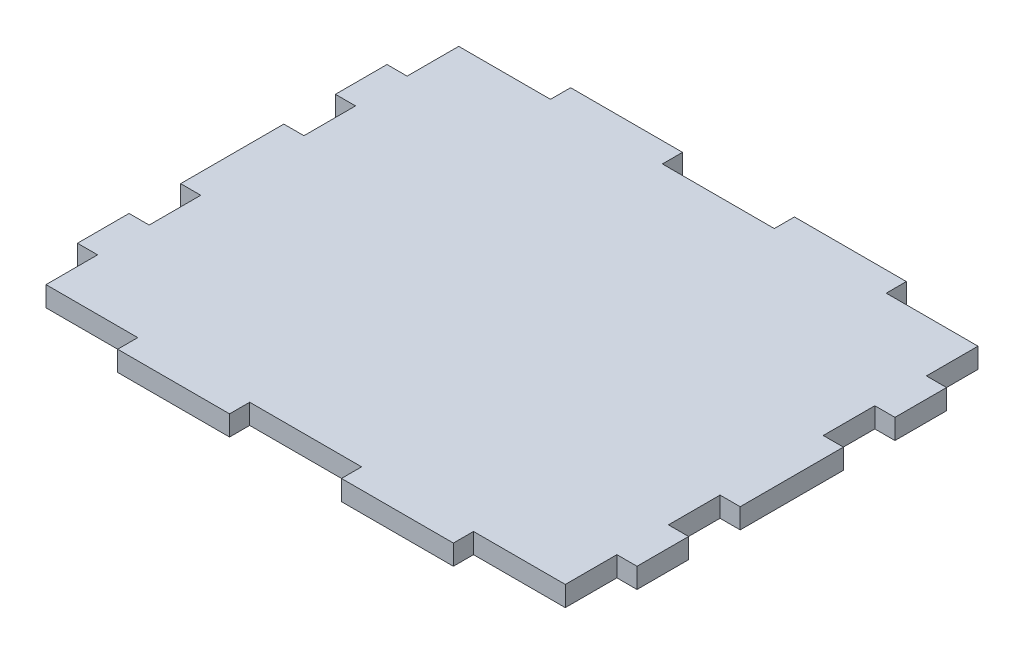
SolidWorks part; units mm, degrees
ref_plane "Front Plane" through (0, 0, 0) normal (0, 0, 1) x (1, 0, 0)
ref_plane "Top Plane" through (0, 0, 0) normal (0, 1, 0) x (1, 0, 0)
ref_plane "Right Plane" through (0, 0, 0) normal (1, 0, 0) x (0, 0, -1)
sketch "Sketch1" plane through (0, 0, 0) normal (0, 1, 0) x (1, 0, 0)
  line L1 (-45.7927, 36.9171) -> (154.7657, 36.9171)
  line L2 (-45.7927, 36.9171) -> (-45.7927, -125.4397)
  line L3 (-45.7927, -125.4397) -> (154.7657, -125.4397)
  line L4 (154.7657, 36.9171) -> (154.7657, -125.4397)
  dimension "D1" = 200.5584
  dimension "D2" = 162.3568
extrude "Boss-Extrude1" add sketch "Sketch1" along normal blind 7.2136
sketch "Sketch2" plane through (0, 7.2136, 0) normal (0, 1, 0) x (1, 0, 0)
  line L0 (54.4865, 36.9171) -> (54.4865, -125.4397) construction
  line L1 (154.7657, 36.9171) -> (-45.7927, 36.9171) construction
  line L2 (-45.7927, -125.4397) -> (154.7657, -125.4397) construction
  line L3 (-45.7927, -44.2613) -> (154.7657, -44.2613) construction
  line L4 (-45.7927, 36.9171) -> (-45.7927, -125.4397) construction
  line L5 (154.7657, -125.4397) -> (154.7657, 36.9171) construction
  line L6 (74.5424, 29.7035) -> (34.4307, 29.7035)
  line L7 (74.5424, -125.4397) -> (34.4307, -125.4397)
  line L8 (54.4865, -125.4397) -> (54.4865, -118.2261)
  line L9 (74.5424, -118.2261) -> (34.4307, -118.2261)
  line L10 (34.4307, -125.4397) -> (34.4307, -118.2261)
  line L11 (34.4307, -125.4397) -> (-5.681, -125.4397)
  line L12 (34.4307, -125.4397) -> (34.4307, -118.2261)
  line L14 (-5.681, -125.4397) -> (-5.681, -118.2261)
  line L15 (-5.681, -125.4397) -> (-45.7927, -125.4397)
  line L16 (-5.681, -125.4397) -> (-5.681, -118.2261)
  line L17 (-5.681, -118.2261) -> (-45.7927, -118.2261)
  line L18 (-45.7927, -125.4397) -> (-45.7927, -118.2261)
  line L19 (-45.7927, -118.2261) -> (-38.5791, -118.2261)
  line L20 (-45.7927, -118.2261) -> (-45.7927, -99.7349)
  line L21 (-45.7927, -99.7349) -> (-38.5791, -99.7349)
  line L22 (-38.5791, -118.2261) -> (-38.5791, -99.7349)
  line L23 (-45.7927, -62.7525) -> (-38.5791, -62.7525)
  line L24 (-45.7927, -62.7525) -> (-45.7927, -81.2437)
  line L25 (-45.7927, -81.2437) -> (-38.5791, -81.2437)
  line L26 (-38.5791, -62.7525) -> (-38.5791, -81.2437)
  line L27 (34.4307, 36.9171) -> (34.4307, 29.7035)
  line L28 (74.5424, 36.9171) -> (34.4307, 36.9171)
  line L29 (54.4865, 36.9171) -> (54.4865, 29.7035)
  line L30 (-5.681, 29.7035) -> (-45.7927, 29.7035)
  line L31 (-45.7927, 36.9171) -> (-45.7927, 29.7035)
  line L32 (-5.681, 36.9171) -> (-45.7927, 36.9171)
  line L33 (-5.681, 36.9171) -> (-5.681, 29.7035)
  line L34 (-45.7927, 11.2123) -> (-38.5791, 11.2123)
  line L35 (-38.5791, 29.7035) -> (-38.5791, 11.2123)
  line L36 (-45.7927, 29.7035) -> (-38.5791, 29.7035)
  line L37 (-45.7927, 29.7035) -> (-45.7927, 11.2123)
  line L38 (-45.7927, -7.2789) -> (-38.5791, -7.2789)
  line L39 (-38.5791, -25.7701) -> (-38.5791, -7.2789)
  line L40 (-45.7927, -25.7701) -> (-38.5791, -25.7701)
  line L41 (-45.7927, -25.7701) -> (-45.7927, -7.2789)
  line L42 (74.5424, -125.4397) -> (74.5424, -118.2261)
  line L43 (114.6541, -118.2261) -> (154.7657, -118.2261)
  line L44 (154.7657, -125.4397) -> (154.7657, -118.2261)
  line L45 (114.6541, -125.4397) -> (154.7657, -125.4397)
  line L46 (114.6541, -125.4397) -> (114.6541, -118.2261)
  line L47 (154.7657, -99.7349) -> (147.5521, -99.7349)
  line L48 (147.5521, -118.2261) -> (147.5521, -99.7349)
  line L49 (154.7657, -118.2261) -> (147.5521, -118.2261)
  line L50 (154.7657, -118.2261) -> (154.7657, -99.7349)
  line L51 (154.7657, -81.2437) -> (147.5521, -81.2437)
  line L52 (147.5521, -62.7525) -> (147.5521, -81.2437)
  line L53 (154.7657, -62.7525) -> (147.5521, -62.7525)
  line L54 (154.7657, -62.7525) -> (154.7657, -81.2437)
  line L55 (154.7657, -25.7701) -> (154.7657, -7.2789)
  line L56 (154.7657, -25.7701) -> (147.5521, -25.7701)
  line L57 (147.5521, -25.7701) -> (147.5521, -7.2789)
  line L58 (154.7657, -7.2789) -> (147.5521, -7.2789)
  line L59 (154.7657, 29.7035) -> (147.5521, 29.7035)
  line L60 (147.5521, 29.7035) -> (147.5521, 11.2123)
  line L61 (154.7657, 11.2123) -> (147.5521, 11.2123)
  line L62 (154.7657, 29.7035) -> (154.7657, 11.2123)
  line L63 (114.6541, 29.7035) -> (154.7657, 29.7035)
  line L64 (114.6541, 36.9171) -> (114.6541, 29.7035)
  line L65 (114.6541, 36.9171) -> (154.7657, 36.9171)
  line L66 (154.7657, 36.9171) -> (154.7657, 29.7035)
  line L67 (74.5424, 36.9171) -> (74.5424, 29.7035)
  point P26 (54.4865, -44.2613)
  line M1 (-45.7927, 36.9171) -> (-45.7927, -125.4397)
  line M2 (-45.7927, -125.4397) -> (154.7657, -125.4397)
  dimension "D1" = 7.2136
  dimension "D2" = 7.2136
  dimension "D3" = 40.1117
  dimension "D4" = 20.0558
  dimension "D5" = 40.1117
  dimension "D6" = 7.2136
  dimension "D7" = 7.2136
  dimension "D8" = 18.4912
  dimension "D9" = 18.4912
  dimension "D10" = 18.4912
  dimension "D11" = 18.4912
extrude "Cut-Extrude1" cut sketch "Sketch2" against normal through all contours L26 L23 L25 M1 | L17 L22 L21 M1 | L14 L17 M1 M2 | L7 L42 L9 L8 | L10 L8 L9 M2 | L44 L45 L46 L43 | L50 L47 L48 L49 | L51 L52 L53 L54 | L55 L58 L57 L56 | L59 L60 L61 L62 | L66 L65 L64 L63 | L28 L27 L6 L67 | L38 L39 L40 L41 | L37 L34 L35 L36 | L31 L32 L33 L30
equation "\"D1@Sketch1\"=\"Base Length@Assembled Container.Assembly\""
equation "\"D2@Sketch1\"=\"Base Width@Assembled Container.Assembly\""
equation "\"D1@Boss-Extrude1\"=\"Acrylic Thickness@Assembled Container.Assembly\""
equation "\"D1@Sketch2\"=\"Acrylic Thickness@Assembled Container.Assembly\""
equation "\"D2@Sketch2\"=\"Acrylic Thickness@Assembled Container.Assembly\""
equation "\"D4@Sketch2\"=\"Lid Long Side Inner Cutout@Assembled Container.Assembly\""
equation "\"D3@Sketch2\"=\"Lid Long Side Outer Cutout@Assembled Container.Assembly\""
equation "\"D6@Sketch2\"=\"Acrylic Thickness@Assembled Container.Assembly\""
equation "\"D7@Sketch2\"=\"Acrylic Thickness@Assembled Container.Assembly\""
equation "\"D8@Sketch2\"=\"Lid Short Side Outer Cutout@Assembled Container.Assembly\""
equation "\"D9@Sketch2\"=\"Lid Short Side Outer Overhang@Assembled Container.Assembly\""
equation "\"D10@Sketch2\"=\"Lid Short Side Middle Cutout@Assembled Container.Assembly\""
